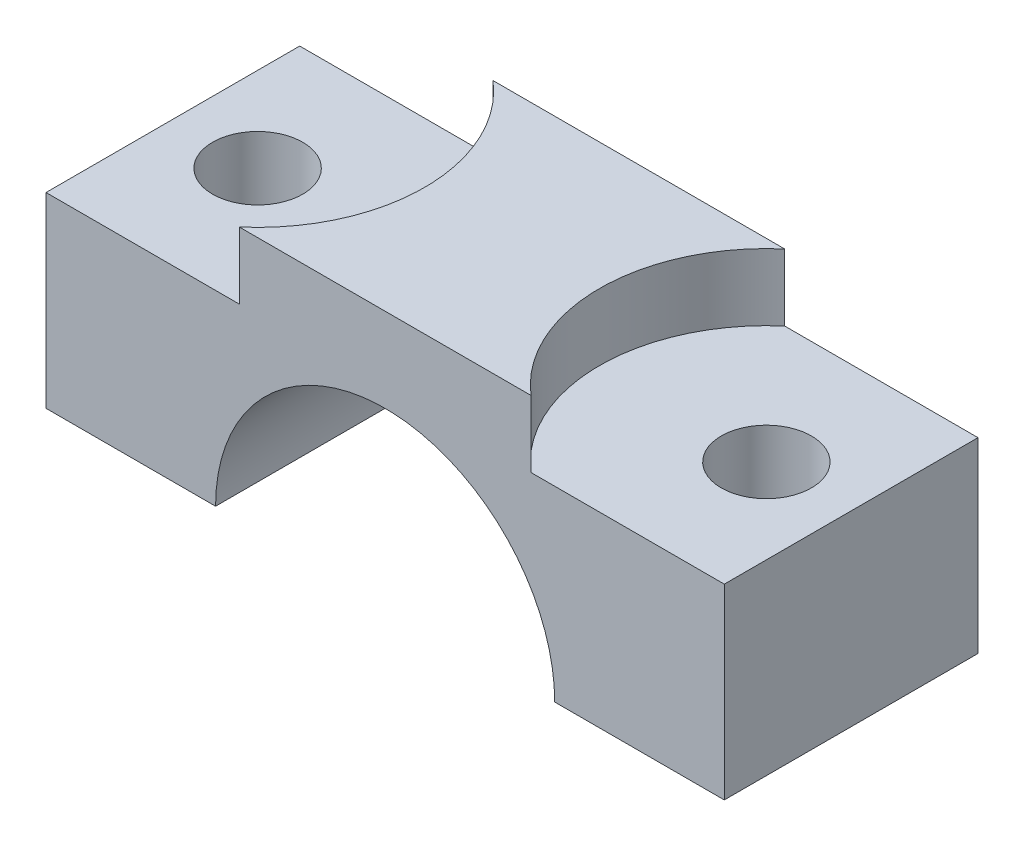
SolidWorks part; units mm, degrees
ref_plane "Front Plane" through (0, 0, 0) normal (0, 0, 1) x (1, 0, 0)
ref_plane "Top Plane" through (0, 0, 0) normal (0, 1, 0) x (1, 0, 0)
ref_plane "Right Plane" through (0, 0, 0) normal (1, 0, 0) x (0, 0, -1)
sketch "Sketch1" plane through (0, 0, 0) normal (0, 0, 1) x (1, 0, 0)
  line L0 (12.7, 0) -> (25.4, 0)
  line L5 (-25.4, 0) -> (-12.7, 0)
  line L6 (-25.4, 0) -> (-25.4, 19)
  line L7 (-25.4, 19) -> (25.4, 19)
  line L8 (25.4, 0) -> (25.4, 19)
  arc A0 (-12.7, 0) -> (12.7, 0) centre (0, 0) cw
  point P5 (0, 19)
  dimension "D3" = 12.7
  dimension "D1" = 50.8
  dimension "D2" = 19
extrude "Boss-Extrude1" add sketch "Sketch1" along normal mid plane 19
sketch "Sketch2" plane through (0, 0, 0) normal (0, -1, 0) x (1, 0, 0)
  line L0 (-25.4, 0) -> (-12.7, 0) construction
  line L1 (-25.4, 9.5) -> (-25.4, -9.5) construction
  line L2 (-12.7, 9.5) -> (-12.7, -9.5) construction
  line L3 (12.7, 0) -> (25.4, 0) construction
  line L4 (12.7, 9.5) -> (12.7, -9.5) construction
  line L5 (25.4, 9.5) -> (25.4, -9.5) construction
  point P12 (-19.05, 0)
  point P13 (19.05, 0)
hole_wizard "CBORE for M12 Hex Head Cap Screw2" positions "Sketch5" profile "Sketch6" counterbore size "M12" standard "ISO" end condition through all
sketch "Sketch5" plane through (0, 19, 0) normal (0, 1, 0) x (1, 0, 0)
  point P0 (-19.05, 0)
  point P3 (19.05, 0)
sketch "Sketch6" plane through (-19.05, 19, 0) normal (1, 0, 0) x (0, 0, 1)
  line L0 (0, 0) -> (0, 19)
  line L1 (0, 19) -> (3.375, 19)
  line L3 (3.375, 19) -> (3.375, 5)
  line L4 (3.375, 5) -> (12.5, 5)
  line L5 (12.5, 5) -> (12.5, 0)
  line L7 (12.5, 0) -> (0, 0)
  line L11 (0, -6.35) -> (0, 107.95) construction
  dimension "Thru Hole Dia." = 6.75
  dimension "Thru Hole Depth" = 19
  dimension "C'Bore Dia." = 25
  dimension "C'Bore Depth" = 5
